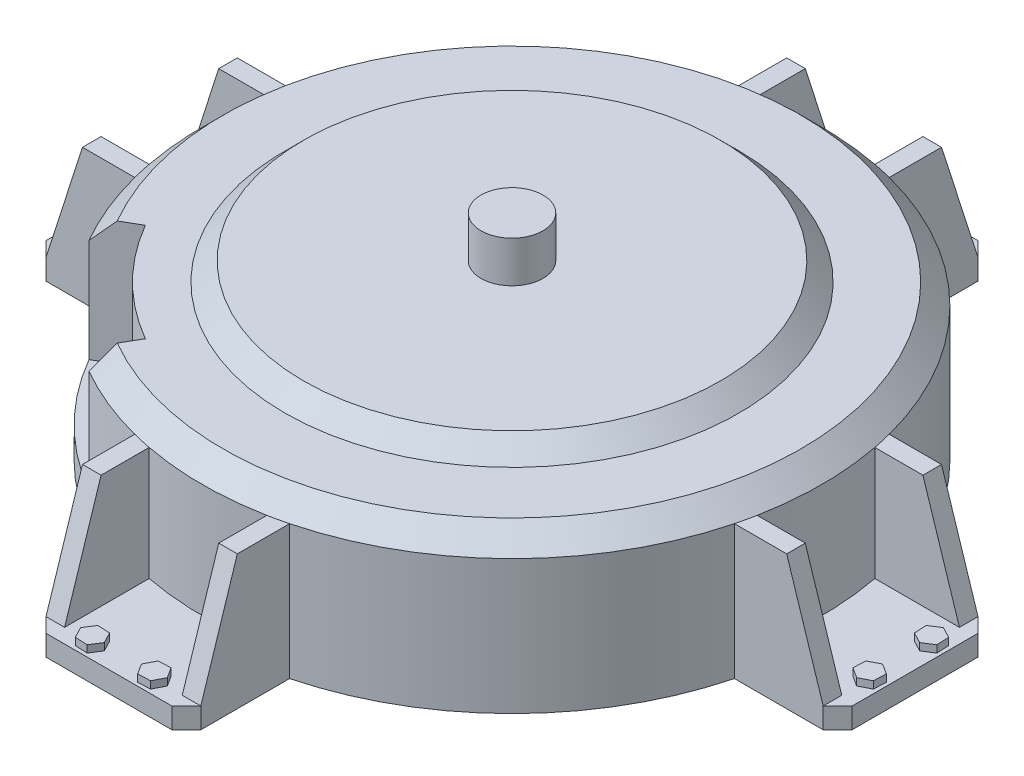
SolidWorks part; units mm, degrees
ref_plane "Front Plane" through (0, 0, 0) normal (0, 0, 1) x (1, 0, 0)
ref_plane "Top Plane" through (0, 0, 0) normal (0, 1, 0) x (1, 0, 0)
ref_plane "Right Plane" through (0, 0, 0) normal (1, 0, 0) x (0, 0, -1)
sketch "Sketch1" plane through (0, 0, 0) normal (0, 1, 0) x (1, 0, 0)
  circle A0 centre (0, 0) radius 150
  dimension "D1" = 300
extrude "Boss-Extrude1" add sketch "Sketch1" along normal blind 75
chamfer "Chamfer1" distance 10 angle 45 1 edges at (0, 75, 150)
sketch "Sketch2" plane through (0, 75, 0) normal (0, 1, 0) x (1, 0, 0)
  line L0 (0, 0) -> (-212.3101, 0) construction
  line L1 (-145.2369, 37.5) -> (-195.2369, 37.5)
  line L2 (-195.2369, 37.5) -> (-195.2369, -37.5)
  line L3 (-195.2369, -37.5) -> (-145.2369, -37.5)
  circle A0 centre (0, 0) radius 150 construction
  arc A1 (-145.2369, 37.5) -> (-145.2369, -37.5) centre (0, 0) ccw
  dimension "D1" = 75
  dimension "D2" = 50
extrude "Boss-Extrude2" add sketch "Sketch2" along normal blind 10 from offset 75 offset against normal yes
chamfer "Chamfer2" distance 7 angle 45 2 edges at (-195.2369, 5, -37.5) (-195.2369, 5, 37.5)
sketch "Sketch4" plane through (0, 0, 37.5) normal (0, 0, 1) x (1, 0, 0)
  line L0 (-188.2369, 10) -> (-145.2369, 10)
  line L1 (-145.2369, 10) -> (-145.2369, 65)
  line L2 (-150, 65) -> (150, 65) construction
  line L3 (-145.2369, 65) -> (-170.5569, 65)
  line L4 (-170.5569, 65) -> (-188.2369, 10)
  dimension "D1" = 17.68
extrude "Boss-Extrude3" add sketch "Sketch4" against normal blind 9
sketch "Sketch5" plane through (0, 10, 0) normal (0, 1, 0) x (1, 0, 0)
  line L0 (-150, 0) -> (-225.6944, 0) construction
  line L1 (-188.2369, 37.5) -> (-188.2369, -37.5) construction
  line L3 (-183.174, -11.7692) -> (-188.5033, -9)
  line L4 (-188.5033, -9) -> (-193.5663, -12.2308)
  line L5 (-193.5663, -12.2308) -> (-193.2998, -18.2308)
  line L6 (-193.2998, -18.2308) -> (-187.9704, -21)
  line L7 (-187.9704, -21) -> (-182.9075, -17.7692)
  line L8 (-182.9075, -17.7692) -> (-183.174, -11.7692)
  arc A0 (-145.2369, -37.5) -> (-147.2676, -28.5) centre (0, 0) ccw construction
  arc A1 (-145.2369, 37.5) -> (-147.2676, -28.5) centre (0, 0) ccw construction
  circle A2 centre (-188.2369, -15) radius 5.2013 construction
  dimension "D1" = 6
  dimension "D2" = 13.5
extrude "Boss-Extrude4" add sketch "Sketch5" along normal blind 3.5
mirror "Mirror1" about plane through (0, 0, 0) normal (0, 0, 1) of "Boss-Extrude3", "Boss-Extrude4"
pattern_circular "CirPattern2" count 4 over 360 about axis through (0, 0, 0) along (0, 1, 0) of "Mirror1", "Boss-Extrude4", "Boss-Extrude3", "Chamfer2", "Boss-Extrude2"
sketch "Sketch6" plane through (0, 75, 0) normal (0, 1, 0) x (1, 0, 0)
  line L2 (-112.5833, -65) -> (-129.9038, -75)
  line L3 (-65, -112.5833) -> (-75, -129.9038)
  arc A1 (-145.2369, -37.5) -> (-37.5, -145.2369) centre (0, 0) ccw construction
  arc A2 (-129.9038, -75) -> (-75, -129.9038) centre (0, 0) ccw
  arc A3 (-112.5833, -65) -> (-65, -112.5833) centre (0, 0) ccw
extrude "Cut-Extrude2" cut sketch "Sketch6" against normal blind 60
sketch "Sketch7" plane through (0, 75, 0) normal (0, 1, 0) x (1, 0, 0)
  circle A0 centre (0, 0) radius 110
  dimension "D1" = 220
extrude "Boss-Extrude5" add sketch "Sketch7" along normal blind 9 draft 45
sketch "Sketch8" plane through (0, 84, 0) normal (0, 1, 0) x (1, 0, 0)
  circle A0 centre (0, 0) radius 15
  dimension "D1" = 30
extrude "Boss-Extrude6" add sketch "Sketch8" along normal blind 20
